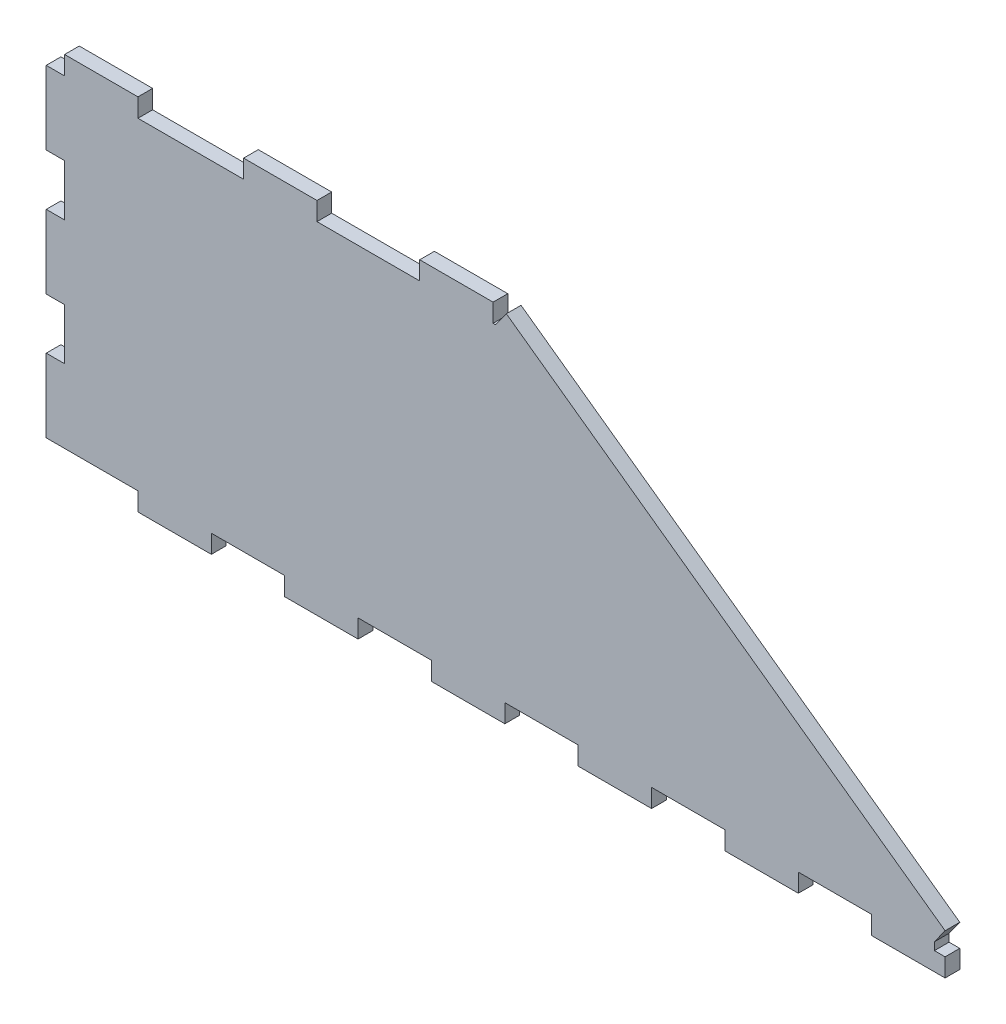
SolidWorks part; units mm, degrees
ref_plane "Front Plane" through (0, 0, 0) normal (0, 0, 1) x (1, 0, 0)
ref_plane "Top Plane" through (0, 0, 0) normal (0, 1, 0) x (1, 0, 0)
ref_plane "Right Plane" through (0, 0, 0) normal (1, 0, 0) x (0, 0, -1)
sketch "Sketch1" plane through (-5.3296, -16.203, 0) normal (0, 0, 1) x (1, 0, 0)
  line L0 (-139.4125, -47.2066) -> (-139.4125, -165.2411) construction
  line L1 (-294.9875, -47.2066) -> (-294.9875, -40.8566) construction
  line L2 (-294.9875, -47.2066) -> (-294.9875, -165.2411)
  line L3 (-294.9875, -165.2411) -> (16.1625, -165.2411)
  line L4 (16.1625, -158.8911) -> (16.1625, -165.2411)
  line L5 (-105.6158, -63.6519) -> (-109.3189, -68.8103) construction
  line L6 (-294.9875, -158.8911) -> (16.1625, -158.8911)
  line L7 (16.1625, -158.8911) -> (-139.4125, -47.2066)
  line L8 (-139.4125, -47.2066) -> (-294.9875, -47.2066)
  line L9 (16.1625, -158.8911) -> (16.1625, -151.0743) construction
  line L10 (-135.7094, -42.0482) -> (16.1625, -151.0743)
  line L11 (-139.4125, -47.2066) -> (-139.4125, -39.334)
  line L12 (-139.4125, -39.334) -> (-288.6375, -40.7811) construction
  line L13 (-288.6375, -165.2411) -> (-288.6375, -40.7811)
  line L14 (-139.4125, -47.2066) -> (-135.7094, -42.0482)
  line L15 (-139.4125, -39.334) -> (-135.7094, -42.0482) construction
  line L16 (16.1625, -151.0743) -> (12.4593, -156.2327)
  line L17 (-135.7094, -42.0482) -> (-139.4125, -39.334)
  line L18 (16.1625, -151.0743) -> (16.1625, -165.2411)
  line L19 (12.4593, -156.2327) -> (12.4593, -158.8911)
  line L21 (-288.6375, -165.2411) -> (-263.2375, -165.2411)
  line L22 (-288.6375, -165.2411) -> (-288.6375, -158.8911)
  line L23 (-288.6375, -158.8911) -> (-263.2375, -158.8911)
  line L24 (-263.2375, -165.2411) -> (-263.2375, -158.8911)
  line L25 (-237.8375, -158.8911) -> (-212.4375, -158.8911)
  line L26 (-237.8375, -158.8911) -> (-237.8375, -165.2411)
  line L27 (-237.8375, -165.2411) -> (-212.4375, -165.2411)
  line L28 (-212.4375, -158.8911) -> (-212.4375, -165.2411)
  line L29 (-187.0375, -158.8911) -> (-161.6375, -158.8911)
  line L30 (-187.0375, -158.8911) -> (-187.0375, -165.2411)
  line L31 (-187.0375, -165.2411) -> (-161.6375, -165.2411)
  line L32 (-161.6375, -158.8911) -> (-161.6375, -165.2411)
  line L33 (-136.2375, -158.8911) -> (-110.8375, -158.8911)
  line L34 (-136.2375, -158.8911) -> (-136.2375, -165.2411)
  line L35 (-136.2375, -165.2411) -> (-110.8375, -165.2411)
  line L36 (-110.8375, -158.8911) -> (-110.8375, -165.2411)
  line L37 (-85.4375, -158.8911) -> (-60.0375, -158.8911)
  line L38 (-85.4375, -158.8911) -> (-85.4375, -165.2411)
  line L39 (-85.4375, -165.2411) -> (-60.0375, -165.2411)
  line L40 (-60.0375, -158.8911) -> (-60.0375, -165.2411)
  line L41 (-34.6375, -158.8911) -> (-9.2375, -158.8911)
  line L42 (-34.6375, -158.8911) -> (-34.6375, -165.2411)
  line L43 (-34.6375, -165.2411) -> (-9.2375, -165.2411)
  line L44 (-9.2375, -158.8911) -> (-9.2375, -165.2411)
  line L45 (-294.9875, -47.2066) -> (-288.6375, -47.2066)
  line L46 (-294.9875, -47.2066) -> (-294.9875, -72.6066)
  line L47 (-294.9875, -72.6066) -> (-288.6375, -72.6066)
  line L48 (-288.6375, -47.2066) -> (-288.6375, -72.6066)
  line L49 (-294.9875, -90.3866) -> (-288.6375, -90.3866)
  line L50 (-294.9875, -90.3866) -> (-294.9875, -115.7866)
  line L51 (-294.9875, -115.7866) -> (-288.6375, -115.7866)
  line L52 (-288.6375, -90.3866) -> (-288.6375, -115.7866)
  line L53 (-294.9875, -133.4911) -> (-288.6375, -133.4911)
  line L54 (-294.9875, -133.4911) -> (-294.9875, -158.8911)
  line L55 (-294.9875, -158.8911) -> (-288.6375, -158.8911)
  line L56 (-288.6375, -133.4911) -> (-288.6375, -158.8911)
  line L57 (-288.6375, -40.7811) -> (-263.2375, -40.7811)
  line L58 (-288.6375, -40.7811) -> (-288.6375, -47.2066)
  line L59 (-288.6375, -47.2066) -> (-263.2375, -47.2066)
  line L60 (-263.2375, -40.7811) -> (-263.2375, -47.2066)
  line L61 (-226.6615, -47.2066) -> (-201.2615, -47.2066)
  line L62 (-226.6615, -47.2066) -> (-226.6615, -40.8566)
  line L63 (-226.6615, -40.8566) -> (-201.2615, -40.8566)
  line L64 (-201.2615, -47.2066) -> (-201.2615, -40.8566)
  line L65 (-165.7015, -47.2066) -> (-140.3015, -47.2066)
  line L66 (-165.7015, -47.2066) -> (-165.7015, -40.8566)
  line L67 (-165.7015, -40.8566) -> (-140.3015, -40.8566)
  line L68 (-140.3015, -47.2066) -> (-140.3015, -40.8566)
  point P32 (-161.6375, -162.0661)
  dimension "D1" = 6.35
  dimension "D2" = 311.15
  dimension "D3" = 6.35
  dimension "D4" = 6.35
  dimension "D5" = 6.35
  dimension "D6" = 124.46
  dimension "D7" = 25.4
  dimension "D8" = 25.4
  dimension "D9" = 25.4
  dimension "D10" = 25.4
  dimension "D11" = 25.4
  dimension "D12" = 25.4
  dimension "D13" = 25.4
  dimension "D14" = 25.4
  dimension "D15" = 25.4
  dimension "D16" = 25.4
  dimension "D17" = 25.4
  dimension "D18" = 25.4
  dimension "D19" = 25.4
  dimension "D20" = 25.4
  dimension "D21" = 17.78
  dimension "D22" = 25.4
  dimension "D23" = 36.576
  dimension "D24" = 6.35
  dimension "D25" = 25.4
  dimension "D26" = 35.56
  dimension "D27" = 25.4
  dimension "D28" = 6.35
extrude "Boss-Extrude1" add sketch "Sketch1" along normal blind 5.08 contours L19 L7 L8 L13 L6 | L13 L8 L11 L12 | L16 L10 L14 L7 | L6 L44 L3 L4 | L42 L6 L40 L3 | L38 L6 L36 L3 | L34 L6 L32 L3 | L30 L6 L28 L3 | L26 L6 L24 L3 | L53 L2 L6 L13 | L2 L51 L13 L49 | L2 L47 L13 L8 | L8 L64 L63 L62 | L8 L68 L67 L66
